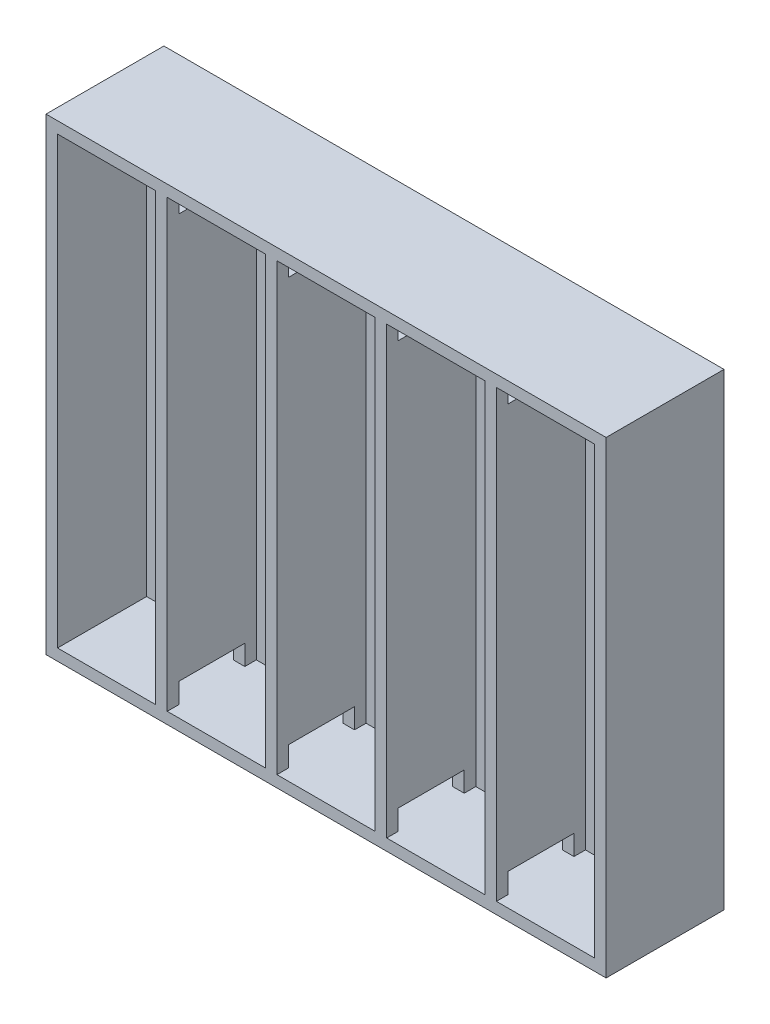
SolidWorks part; units mm, degrees
ref_plane "Front Plane" through (0, 0, 0) normal (0, 0, 1) x (1, 0, 0)
ref_plane "Top Plane" through (0, 0, 0) normal (0, 1, 0) x (1, 0, 0)
ref_plane "Right Plane" through (0, 0, 0) normal (1, 0, 0) x (0, 0, -1)
sketch "Sketch1" plane through (0, 0, 0) normal (0, 0, 1) x (1, 0, 0)
  line L1 (0, 0) -> (95.1927, 0)
  line L2 (0, 0) -> (0, -77.236)
  line L3 (0, -77.236) -> (95.1927, -77.236)
  line L4 (95.1927, 0) -> (95.1927, -77.236)
  point P5 (95.1927, -77.236)
extrude "Boss-Extrude1" add sketch "Sketch1" along normal blind 5 contours L1 L4 L3 L2
sketch "Sketch2" plane through (0, 0, 0) normal (-1, 0, 0) x (0, 0, 1)
  line L0 (5, -77.236) -> (0, -77.236) construction
  line L1 (0, 0) -> (20.4583, 0)
  line L2 (0, 0) -> (0, -77.236)
  line L3 (0, -77.236) -> (20.4583, -77.236)
  line L4 (20.4583, 0) -> (20.4583, -77.236)
extrude "Boss-Extrude2" add sketch "Sketch2" along normal blind 2
sketch "Sketch3" plane through (0, 0, 0) normal (0, 1, 0) x (1, 0, 0)
  line L0 (95.1927, -5) -> (95.1927, 0) construction
  line L1 (-2, 0) -> (95.1927, 0)
  line L2 (-2, 0) -> (-2, -20.4583)
  line L3 (-2, -20.4583) -> (95.1927, -20.4583)
  line L4 (95.1927, 0) -> (95.1927, -20.4583)
extrude "Boss-Extrude3" add sketch "Sketch3" along normal blind 2
sketch "Sketch4" plane through (0, -77.236, 0) normal (0, -1, 0) x (1, 0, 0)
  line L1 (-2, 20.4583) -> (95.1927, 20.4583)
  line L2 (-2, 20.4583) -> (-2, 0)
  line L3 (-2, 0) -> (95.1927, 0)
  line L4 (95.1927, 20.4583) -> (95.1927, 0)
extrude "Boss-Extrude4" add sketch "Sketch4" along normal blind 2
pattern_linear "LPattern1" count 6 spacing 19.0385 along (1, 0, 0) of "Boss-Extrude2"
sketch "Sketch7" plane through (17.0385, 0, 0) normal (-1, 0, 0) x (0, 0, 1)
  line L4 (20.4583, 0) -> (5, 0)
  line L5 (5, 0) -> (5, -77.236)
  line L6 (5, -77.236) -> (20.4583, -77.236)
  line L7 (20.4583, -77.236) -> (20.4583, 0)
  line L8 (20.4583, 0) -> (5, 0)
  line L9 (5, 0) -> (5, -77.236)
  line L10 (5, -77.236) -> (20.4583, -77.236)
  line L11 (20.4583, -77.236) -> (20.4583, 0)
  line L13 (7, 0) -> (18.4583, 0)
  line L14 (7, 0) -> (7, -3.5)
  line L15 (7, -3.5) -> (18.4583, -3.5)
  line L16 (18.4583, 0) -> (18.4583, -3.5)
  line L17 (18.4583, -77.236) -> (7, -77.236)
  line L18 (18.4583, -77.236) -> (18.4583, -73.736)
  line L19 (18.4583, -73.736) -> (7, -73.736)
  line L20 (7, -77.236) -> (7, -73.736)
  dimension "D2" = 3.5
  dimension "D3" = 2
  dimension "D4" = 2
  dimension "D1" = 0
extrude "Cut-Extrude1" cut sketch "Sketch7" against normal up to surface (59.1156 mm away) contours L16 L8 L14 L15 | L19 L20 L17 L18 up to face at (76.1542, -38.618, 12.7292)
